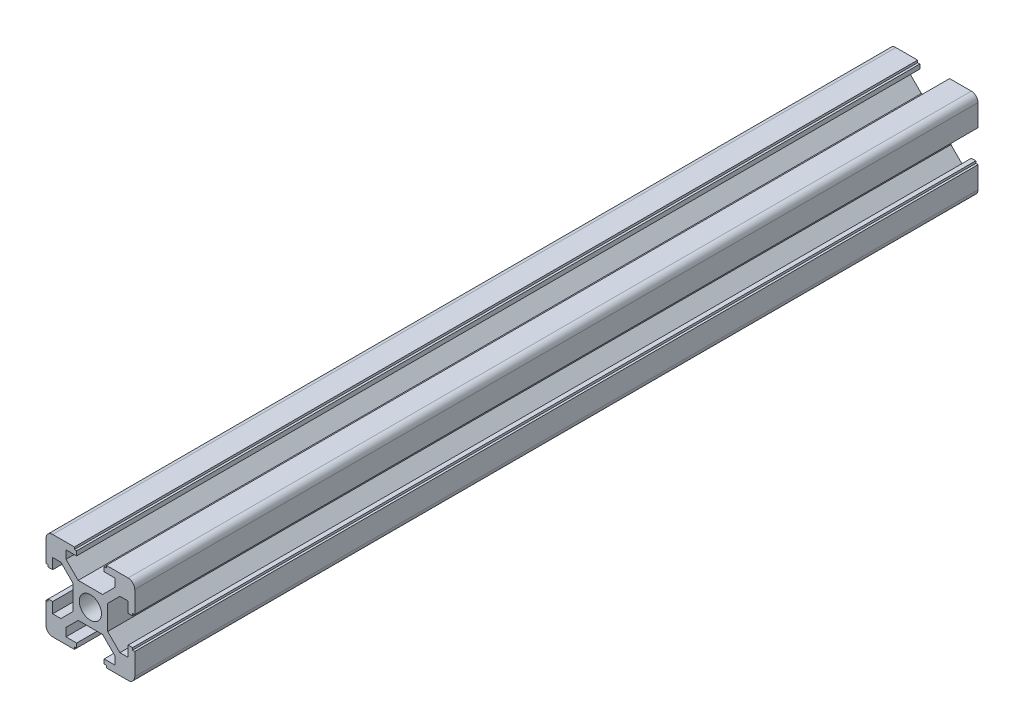
SolidWorks part; units mm, degrees
ref_plane "前视基准面" through (0, 0, 0) normal (0, 0, 1) x (1, 0, 0)
ref_plane "上视基准面" through (0, 0, 0) normal (0, 1, 0) x (1, 0, 0)
ref_plane "右视基准面" through (0, 0, 0) normal (1, 0, 0) x (0, 0, -1)
other "Configuration Table"
sketch "草图2" plane through (0, 0, 0) normal (0, 0, 1) x (1, 0, 0)
  line L0 (-3.6, 10) -> (-3.6, 9.5)
  line L1 (-3.6, 9.5) -> (-3.1, 9.5)
  line L2 (-3.1, 9.5) -> (-3.1, 8.5)
  line L3 (-3.1, 8.5) -> (-5.5, 8.5)
  line L4 (-8.5, -10) -> (-3.6, -10)
  line L5 (-10, -8.5) -> (-10, -3.6)
  line L6 (8.5, 10) -> (3.6, 10)
  line L7 (10, 8.5) -> (10, 3.6)
  line L8 (0, 14.8756) -> (0, 0) construction
  line L9 (0, 0) -> (14.1675, 0) construction
  line L10 (-5.5, 8.5) -> (-5.5, 6.65)
  line L11 (-5.5, 6.65) -> (-2.75, 3.9)
  line L12 (-2.75, 3.9) -> (2.75, 3.9)
  line L13 (5.5, 6.65) -> (2.75, 3.9)
  line L14 (5.5, 8.5) -> (5.5, 6.65)
  line L15 (3.1, 8.5) -> (5.5, 8.5)
  line L16 (3.1, 9.5) -> (3.1, 8.5)
  line L17 (3.6, 9.5) -> (3.1, 9.5)
  line L18 (3.6, 10) -> (3.6, 9.5)
  line L19 (-3.6, 10) -> (-8.5, 10)
  line L20 (10, 3.6) -> (9.5, 3.6)
  line L21 (9.5, 3.6) -> (9.5, 3.1)
  line L22 (9.5, 3.1) -> (8.5, 3.1)
  line L23 (8.5, 3.1) -> (8.5, 5.5)
  line L24 (8.5, 5.5) -> (6.65, 5.5)
  line L25 (6.65, 5.5) -> (3.9, 2.75)
  line L26 (3.9, 2.75) -> (3.9, -2.75)
  line L27 (6.65, -5.5) -> (3.9, -2.75)
  line L28 (8.5, -5.5) -> (6.65, -5.5)
  line L29 (8.5, -3.1) -> (8.5, -5.5)
  line L30 (9.5, -3.1) -> (8.5, -3.1)
  line L31 (9.5, -3.6) -> (9.5, -3.1)
  line L32 (10, -3.6) -> (9.5, -3.6)
  line L33 (3.6, -10) -> (3.6, -9.5)
  line L34 (3.6, -9.5) -> (3.1, -9.5)
  line L35 (3.1, -9.5) -> (3.1, -8.5)
  line L36 (3.1, -8.5) -> (5.5, -8.5)
  line L37 (5.5, -8.5) -> (5.5, -6.65)
  line L38 (5.5, -6.65) -> (2.75, -3.9)
  line L39 (2.75, -3.9) -> (-2.75, -3.9)
  line L40 (-5.5, -6.65) -> (-2.75, -3.9)
  line L41 (-5.5, -8.5) -> (-5.5, -6.65)
  line L42 (-3.1, -8.5) -> (-5.5, -8.5)
  line L43 (-3.1, -9.5) -> (-3.1, -8.5)
  line L44 (-3.6, -9.5) -> (-3.1, -9.5)
  line L45 (-3.6, -10) -> (-3.6, -9.5)
  line L46 (-10, -3.6) -> (-9.5, -3.6)
  line L47 (-9.5, -3.6) -> (-9.5, -3.1)
  line L48 (-9.5, -3.1) -> (-8.5, -3.1)
  line L49 (-8.5, -3.1) -> (-8.5, -5.5)
  line L50 (-8.5, -5.5) -> (-6.65, -5.5)
  line L51 (-6.65, -5.5) -> (-3.9, -2.75)
  line L52 (-3.9, -2.75) -> (-3.9, 2.75)
  line L53 (-6.65, 5.5) -> (-3.9, 2.75)
  line L54 (-8.5, 5.5) -> (-6.65, 5.5)
  line L55 (-8.5, 3.1) -> (-8.5, 5.5)
  line L56 (-9.5, 3.1) -> (-8.5, 3.1)
  line L57 (-9.5, 3.6) -> (-9.5, 3.1)
  line L58 (-10, 3.6) -> (-9.5, 3.6)
  line L59 (3.6, -10) -> (8.5, -10)
  line L60 (-10, 3.6) -> (-10, 8.5)
  line L61 (10, -3.6) -> (10, -8.5)
  circle A0 centre (0, 0) radius 2.5
  arc A1 (-10, 8.5) -> (-8.5, 10) centre (-8.5, 8.5) cw
  arc A2 (10, 8.5) -> (8.5, 10) centre (8.5, 8.5) ccw
  arc A3 (-8.5, -10) -> (-10, -8.5) centre (-8.5, -8.5) cw
  arc A4 (8.5, -10) -> (10, -8.5) centre (8.5, -8.5) ccw
  point P0 (-10, 0)
  point P1 (10, 0)
  point P2 (0, 10)
  point P3 (0, -10)
  point P4 (0, 0)
  point P5 (-10, -10)
  point P6 (10, -10)
  point P7 (10, 10)
  point P8 (-10, 10)
  point P36 (-10, 10)
  point P39 (10, 10)
  dimension "D1" = 11
  dimension "D2" = 20
  dimension "D3" = 6.2
  dimension "D4" = 7.2
  dimension "D5" = 6.1
  dimension "D6" = 5
  dimension "D7" = 1.5
  dimension "D8" = 45
  dimension "D9" = 0.5
  dimension "D10" = 1
  dimension "D11" = 5.5
extrude "凸台-拉伸1" add sketch "草图2" along normal blind 190
